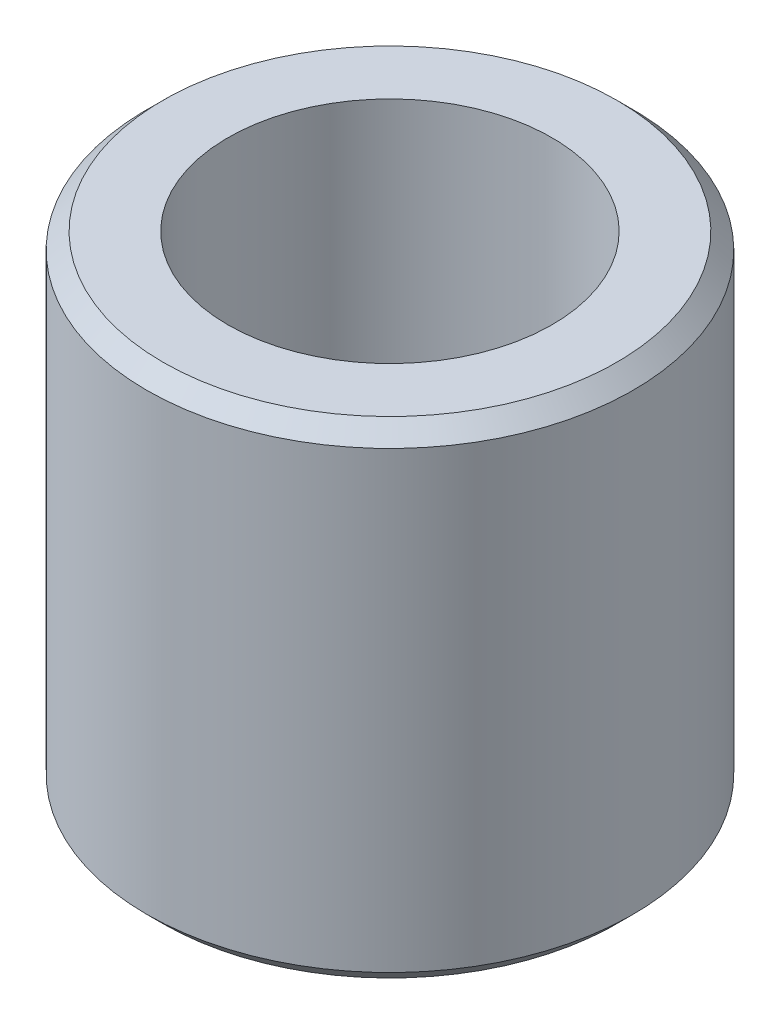
SolidWorks part; units mm, degrees
ref_plane "Front Plane" through (0, 0, 0) normal (0, 0, 1) x (1, 0, 0)
ref_plane "Top Plane" through (0, 0, 0) normal (0, 1, 0) x (1, 0, 0)
ref_plane "Right Plane" through (0, 0, 0) normal (1, 0, 0) x (0, 0, -1)
sketch "Sketch1" plane through (0, 0, 0) normal (0, 1, 0) x (1, 0, 0)
  circle A0 centre (0, 0) radius 15
  circle A1 centre (0, 0) radius 10
  dimension "D1" = 20
  dimension "D2" = 30
extrude "Boss-Extrude1" add sketch "Sketch1" along normal mid plane 30
chamfer "Chamfer1" distance 1 angle 45 2 edges at (0, -15, 15) (0, 15, 15)
